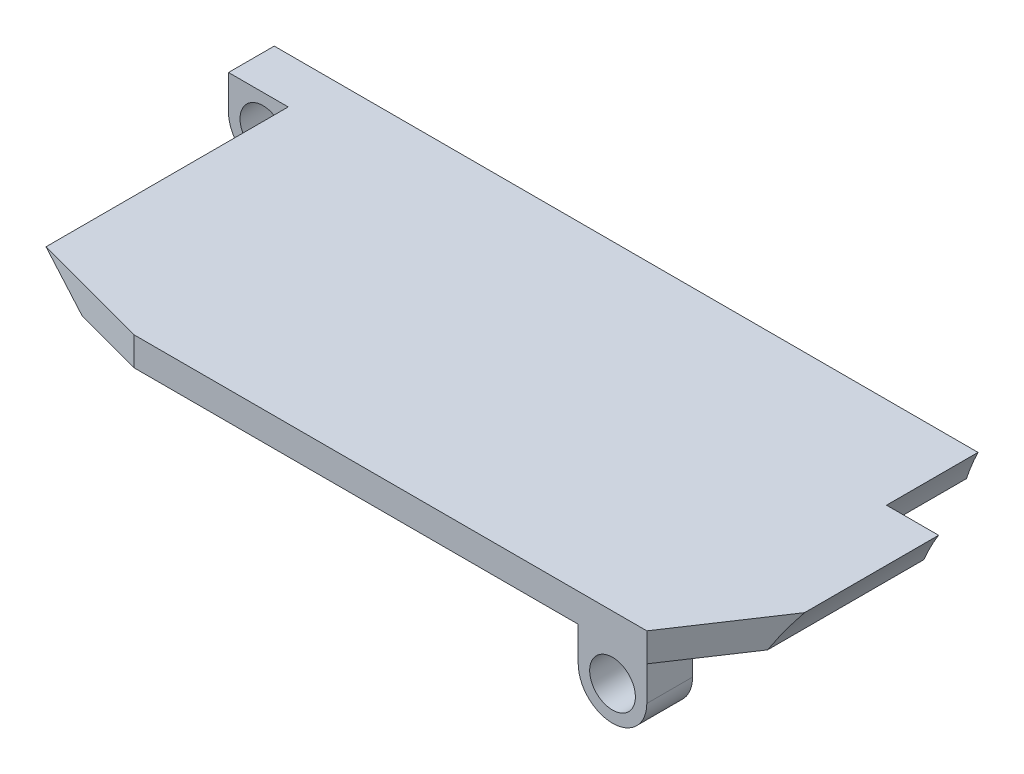
SolidWorks part; units mm, degrees
material "1060-H16"
ref_plane "前视基准面" through (0, 0, 0) normal (0, 0, 1) x (1, 0, 0)
ref_plane "上视基准面" through (0, 0, 0) normal (0, 1, 0) x (1, 0, 0)
ref_plane "右视基准面" through (0, 0, 0) normal (1, 0, 0) x (0, 0, -1)
sketch "草图2" plane through (0, 0, -2) normal (0, 0, -1) x (-1, 0, 0)
  line L0 (15.5849, 24.75) -> (-14.8556, 24.75)
  line L1 (15.5849, 24.75) -> (13.4199, 26)
  line L2 (13.4199, 26) -> (-14.2084, 26)
  arc A2 (-14.8556, 24.75) -> (-14.8556, 34.25) centre (-22.5, 29.5) ccw
  arc A3 (-14.8556, 34.25) -> (-14.8556, 24.75) centre (-22.5, 29.5) ccw
  arc A4 (-14.8556, 24.75) -> (-14.8556, 34.25) centre (-22.5, 29.5) ccw
  arc A5 (-14.8556, 34.25) -> (-14.8556, 24.75) centre (-22.5, 29.5) ccw
  dimension "D1" = 1.25
  dimension "D2" = 30
  dimension "D4" = 30.4405
  dimension "D3" = 0
extrude "凸台-拉伸1" add sketch "草图2" along normal blind 14
sketch "草图3" plane through (0, 0, -16) normal (0, 0, -1) x (-1, 0, 0)
  line L0 (-12.5784, 24.75) -> (-17.3583, 24.75)
  line L1 (-17.3583, 24.75) -> (-16.0628, 32.25)
  line L2 (-16.0628, 32.25) -> (-11.8493, 32.25)
  arc A0 (-12.5784, 24.75) -> (-11.8493, 32.25) centre (-22.5, 29.5) ccw construction
  arc A1 (-12.5784, 24.75) -> (-11.8493, 32.25) centre (-22.5, 29.5) ccw
extrude "切除-拉伸1" cut sketch "草图3" against normal blind 4
sketch "草图4" plane through (0, 24.75, 0) normal (0, -1, 0) x (1, 0, 0)
  line L0 (12.0963, -2) -> (15.4296, -7)
  line L1 (14.8556, -6.1389) -> (12.0963, -2) construction
  line L3 (-15.5849, -2) -> (14.8556, -2) construction
  line L4 (15.4296, -7) -> (15.4296, -2)
  line L7 (-10.3293, -2) -> (-15.5849, -3.4082)
  line L8 (-15.5849, -3.4082) -> (-10.3293, -2) construction
  line L9 (-15.5849, -16) -> (-15.5849, -2) construction
  line L10 (-15.5849, -3.4082) -> (-15.5849, -2)
  line L11 (-15.5849, -2) -> (-10.3293, -2)
  line L12 (15.4296, -2) -> (12.0963, -2)
extrude "切除-拉伸2" cut sketch "草图4" against normal through all
sketch "草图6" plane through (0, 0, -16) normal (0, 0, -1) x (-1, 0, 0)
  line L0 (15.5849, 24.75) -> (18.1957, 24.75)
  line L1 (18.1957, 24.75) -> (18.1957, 26.25)
  line L2 (18.1957, 26.25) -> (15.0857, 26.25)
  line L3 (15.0857, 26.25) -> (13.4199, 26)
  circle A0 centre (16.6957, 26.25) radius 1.5
  line M5 (15.5849, 24.75) -> (13.4199, 26)
  dimension "D3" = 3
  dimension "D4" = 2.6108
  dimension "D1" = 1.5
  dimension "D2" = 3.11
extrude "凸台-拉伸2" add sketch "草图6" against normal blind 2 contours A0 L2 L3 L0 M5 | L2 A0 | A0 L0 L1 | L2 A0
sketch "草图7" plane through (0, 0, -2) normal (0, 0, 1) x (1, 0, 0)
  line L0 (12.0963, 26) -> (12.0963, 27.5)
  line L1 (12.0963, 32.25) -> (12.0963, 24.75) construction
  line L2 (12.0963, 27.5) -> (9.0963, 27.5)
  line L3 (9.0963, 27.5) -> (9.0963, 26)
  line L4 (-10.3293, 26) -> (12.0963, 26) construction
  line L5 (9.0963, 26) -> (12.0963, 26)
  circle A0 centre (10.5963, 27.5) radius 1.5
  line M3 (12.0963, 26) -> (-10.3293, 26)
  dimension "D1" = 3
  dimension "D2" = 1.5
extrude "凸台-拉伸3" add sketch "草图7" against normal blind 2 contours A0 L0 M3 | A0 L3 L5 | L2 A0 | L2 A0
hole_wizard "大小mm 暗销孔1" positions "草图8" profile "草图9" hole size "Ø2.0" standard "GB" end condition through all
sketch "草图8" plane through (0, 0, -16) normal (0, 0, -1) x (-1, 0, 0)
  line L0 (18.1957, 24.75) -> (-12.5784, 24.75) construction
  line L2 (18.1957, 24.75) -> (18.1957, 26.25) construction
  point P0 (16.6918, 26.25)
  dimension "D1" = 1.5
  dimension "D2" = 1.504
sketch "草图9" plane through (-16.6918, 26.25, -16) normal (1, 0, 0) x (0, 1, 0)
  line L0 (0, 0) -> (0, 14)
  line L1 (0, 14) -> (1, 14)
  line L2 (1, 14) -> (1, 0)
  line L5 (1, 0) -> (0, 0)
  line L11 (0, -6.35) -> (0, 107.95) construction
  dimension "通孔孔直径" = 2
  dimension "通孔孔深度" = 14
hole_wizard "大小mm 暗销孔2" positions "草图10" profile "草图11" hole size "Ø2.0" standard "GB" end condition through all
sketch "草图10" plane through (0, 0, -2) normal (0, 0, 1) x (1, 0, 0)
  line L0 (9.0963, 27.5) -> (9.0963, 26) construction
  line L3 (-10.3293, 26) -> (9.0963, 26) construction
  point P0 (10.5963, 27.5)
  dimension "D1" = 1.5
  dimension "D2" = 1.5
sketch "草图11" plane through (10.5963, 27.5, -2) normal (1, 0, 0) x (0, -1, 0)
  line L0 (0, 0) -> (0, 14)
  line L1 (0, 14) -> (1, 14)
  line L2 (1, 14) -> (1, 0)
  line L5 (1, 0) -> (0, 0)
  line L11 (0, -6.35) -> (0, 107.95) construction
  dimension "通孔孔直径" = 2
  dimension "通孔孔深度" = 14
mirror "镜向1" about plane through (0, 0, 0) normal (0, 1, 0) of bodies 107
delete or keep bodies "实体-删除/保留 1" type delete bodies bodies 107
